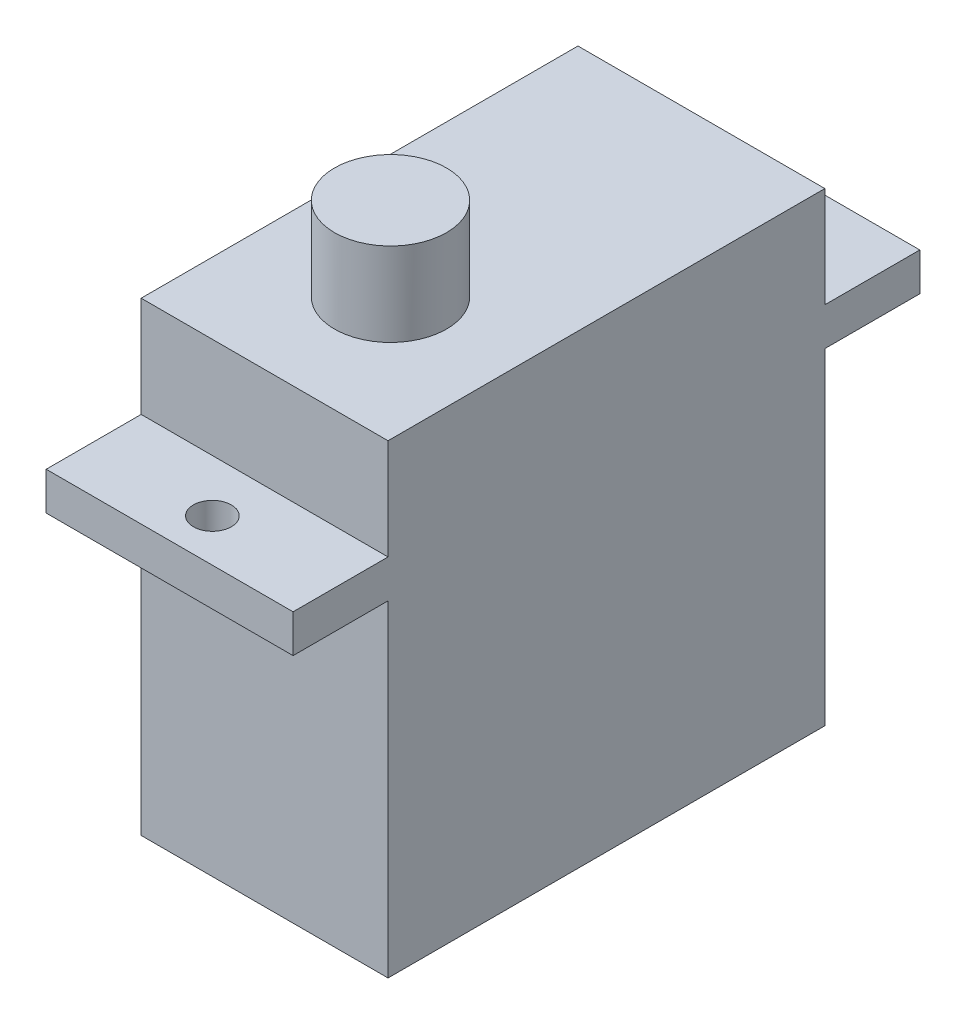
SolidWorks part; units mm, degrees
material "Servo"
ref_plane "前基準面" through (0, 0, 0) normal (0, 0, 1) x (1, 0, 0)
ref_plane "上基準面" through (0, 0, 0) normal (0, 1, 0) x (1, 0, 0)
ref_plane "右基準面" through (0, 0, 0) normal (1, 0, 0) x (0, 0, -1)
sketch "草圖1" plane through (0, 0, 0) normal (1, 0, 0) x (0, 0, -1)
  line L0 (11.5, 10.6) -> (16.5, 10.6)
  line L2 (-11.5, 8.6) -> (-11.5, -8.6)
  line L3 (-11.5, -8.6) -> (11.5, -8.6)
  line L4 (11.5, 8.6) -> (11.5, -8.6)
  line L5 (-11.5, 8.6) -> (11.5, -8.6) construction
  line L6 (-11.5, -8.6) -> (11.5, 8.6) construction
  line L7 (-16.5, 10.6) -> (-11.5, 10.6)
  line L8 (-16.5, 10.6) -> (-16.5, 8.6)
  line L9 (-16.5, 8.6) -> (-11.5, 8.6)
  line L10 (16.5, 10.6) -> (16.5, 8.6)
  line L11 (-16.5, 10.6) -> (16.5, 8.6) construction
  line L12 (-16.5, 8.6) -> (16.5, 10.6) construction
  line L13 (-11.5, 15.9) -> (11.5, 15.9)
  line L14 (-11.5, 15.9) -> (-11.5, 10.6)
  line L16 (11.5, 15.9) -> (11.5, 10.6)
  line L17 (-11.5, 15.9) -> (11.5, 10.6) construction
  line L18 (-11.5, 10.6) -> (11.5, 15.9) construction
  line L19 (11.5, 8.6) -> (16.5, 8.6)
  line L20 (0, 13.25) -> (0, 0) construction
  point P0 (0, 0)
  point P6 (0, 9.6)
  point P11 (0, 13.25)
  dimension "D1" = 23
  dimension "D2" = 19.2
  dimension "D3" = 24.5
  dimension "D4" = 17.2
  dimension "D5" = 33
extrude "填料-伸長1" add sketch "草圖1" along normal blind 13
sketch "草圖2" plane through (0, 15.9, 0) normal (0, 1, 0) x (1, 0, 0)
  line L1 (13, -11.5) -> (0, -11.5) construction
  line L3 (0, 11.5) -> (0, -11.5) construction
  line L4 (13, 11.5) -> (13, -11.5) construction
  line L5 (6.5, -11.5) -> (6.5, 11.5) construction
  line L6 (13, 11.5) -> (0, 11.5) construction
  arc A0 (3.5088, 0.7708) -> (9.4912, 0.7708) centre (6.5, -5) ccw
  arc A1 (9.4912, 0.7708) -> (3.5088, 0.7708) centre (6.5, 1) ccw
  dimension "D1" = 6
  dimension "D2" = 6
sketch "草圖4" plane through (0, 10.6, 0) normal (0, 1, 0) x (1, 0, 0)
  line L0 (6.5, -16.5) -> (6.5, 16.5) construction
  line L1 (13, -16.5) -> (0, -16.5) construction
  line L2 (13, 16.5) -> (0, 16.5) construction
  line L3 (6.5, 14.25) -> (6.5, -14.25) construction
  circle A0 centre (6.5, 14.25) radius 1
  circle A1 centre (6.5, -14.25) radius 1
  point P10 (6.5, -6.9218)
  point P11 (6.5, 4.7938)
  point P12 (6.5, 0)
  point P13 (6.5, 0)
  dimension "D3" = 2
  dimension "D1" = 28.5
extrude "除料-伸長1" cut sketch "草圖4" against normal through all
sketch "草圖6" plane through (0, 15.9, 0) normal (0, 1, 0) x (1, 0, 0)
  line L0 (6.5, -11.5) -> (6.5, 11.5) construction
  circle A0 centre (6.5, -4.87) radius 2.95
  circle A1 centre (6.5, -14.25) radius 1 construction
  dimension "D2" = 5.9
  dimension "D1" = 9.38
extrude "填料-伸長2" add sketch "草圖6" along normal blind 4.4
